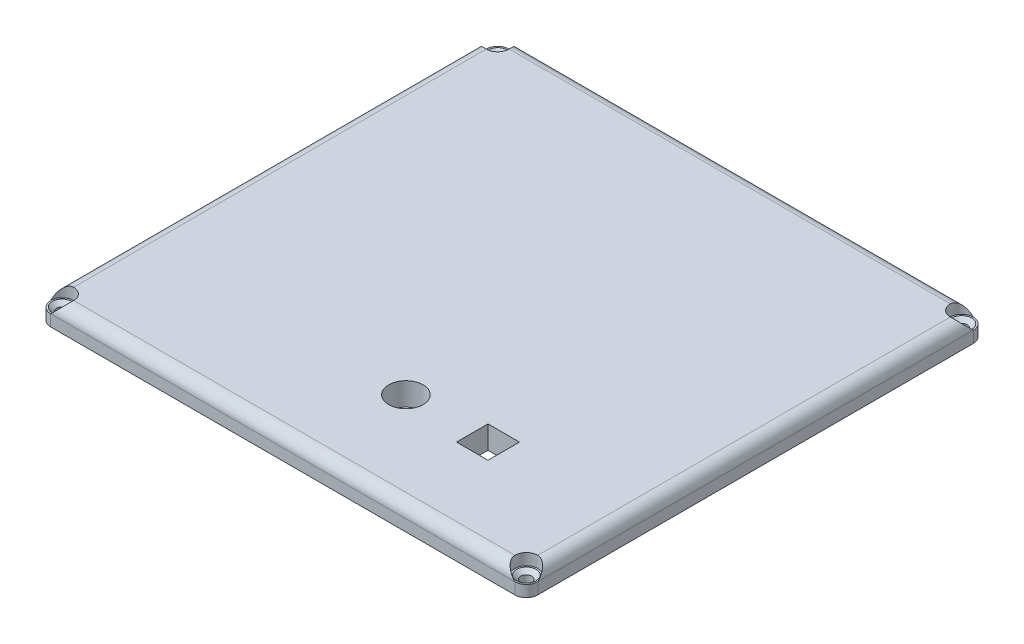
SolidWorks part; units mm, degrees
ref_plane "Front Plane" through (0, 0, 0) normal (0, 0, 1) x (1, 0, 0)
ref_plane "Top Plane" through (0, 0, 0) normal (0, 1, 0) x (1, 0, 0)
ref_plane "Right Plane" through (0, 0, 0) normal (1, 0, 0) x (0, 0, -1)
sketch "Sketch1" plane through (0, 0, 0) normal (0, 1, 0) x (1, 0, 0)
  line L1 (-53.975, -50.8) -> (53.975, -50.8)
  line L2 (-53.975, -50.8) -> (-53.975, 50.8)
  line L3 (-53.975, 50.8) -> (53.975, 50.8)
  line L4 (53.975, -50.8) -> (53.975, 50.8)
  line L5 (-53.975, -50.8) -> (53.975, 50.8) construction
  line L6 (-53.975, 50.8) -> (53.975, -50.8) construction
  point P0 (0, 0)
  dimension "D1" = 107.95
  dimension "D2" = 101.6
extrude "Boss-Extrude1" add sketch "Sketch1" along normal blind 5.08
fillet "Fillet1" radius 2.54 8 edges at (-53.975, 2.54, -50.8) (0, 5.08, -50.8) (-53.975, 5.08, 0) (0, 5.08, 50.8) (53.975, 5.08, 0) (53.975, 2.54, -50.8) (53.975, 2.54, 50.8) (-53.975, 2.54, 50.8)
sketch "Sketch2" plane through (0, 0, 0) normal (0, -1, 0) x (1, 0, 0)
  line L1 (-49.2125, -46.0375) -> (49.2125, -46.0375)
  line L2 (-49.2125, -46.0375) -> (-49.2125, 46.0375)
  line L3 (-49.2125, 46.0375) -> (49.2125, 46.0375)
  line L4 (49.2125, -46.0375) -> (49.2125, 46.0375)
  line L5 (-49.2125, -46.0375) -> (49.2125, 46.0375) construction
  line L6 (-49.2125, 46.0375) -> (49.2125, -46.0375) construction
  line L7 (-46.4973, -43.4975) -> (46.4973, -43.4975)
  line L8 (-46.4973, -43.4975) -> (-46.4973, 43.4975)
  line L9 (-46.4973, 43.4975) -> (46.4973, 43.4975)
  line L10 (46.4973, -43.4975) -> (46.4973, 43.4975)
  line L11 (-46.4973, -43.4975) -> (46.4973, 43.4975) construction
  line L12 (-46.4973, 43.4975) -> (46.4973, -43.4975) construction
  point P0 (0, 0)
  point P6 (0, 0)
  point P11 (49.2125, 46.0375)
  dimension "D3" = 2.54
extrude "Boss-Extrude2" add sketch "Sketch2" along normal blind 2.54
sketch "Sketch3" plane through (0, 0, 0) normal (0, -1, 0) x (1, 0, 0)
  circle A0 centre (6.0087, 29.5186) radius 3.81
  dimension "D1" = 7.62
extrude "Cut-Extrude1" cut sketch "Sketch3" against normal up to surface (5.08 mm away) up to face at (0, 5.08, 0)
sketch "Sketch4" plane through (0, 0, 0) normal (0, -1, 0) x (1, 0, 0)
  line L0 (20.7008, 33.0108) -> (27.6858, 26.0258) construction
  line L1 (20.7008, 33.0108) -> (27.6858, 33.0108)
  line L2 (20.7008, 33.0108) -> (20.7008, 26.0258)
  line L3 (20.7008, 26.0258) -> (27.6858, 26.0258)
  line L4 (27.6858, 33.0108) -> (27.6858, 26.0258)
  point P6 (24.1933, 29.5183)
  point P7 (24.1933, 29.5183)
  dimension "D1" = 6.985
extrude "Cut-Extrude2" cut sketch "Sketch4" against normal up to surface (5.08 mm away) up to face at (6.0087, 5.08, 25.7086)
sketch "Sketch5" plane through (0, 5.08, 0) normal (0, 1, 0) x (1, 0, 0)
  circle A0 centre (-51.435, -48.26) radius 2.54
extrude "Cut-Extrude3" cut sketch "Sketch5" against normal blind 2.54
pattern_linear "LPattern1" count 2 spacing 96.52 along (0, 0, -1) count 2 spacing 102.87 along (1, 0, 0) of "Cut-Extrude3"
hole_wizard "CSK for #2 Flat Head Machine Screw (100)1" positions "Sketch6" profile "Sketch7" countersink size "#2" standard "ANSI Inch" end condition through all
sketch "Sketch6" plane through (0, 2.54, 0) normal (0, 1, 0) x (1, 0, 0)
  point P0 (51.435, -48.26)
  point P3 (-51.435, -48.26)
  point P6 (-51.435, 48.26)
  point P9 (51.435, 48.26)
sketch "Sketch7" plane through (51.435, 2.54, 48.26) normal (1, 0, 0) x (0, 0, 1)
  line L0 (0, 0) -> (0, 5.08)
  line L1 (0, 5.08) -> (1.2192, 5.08)
  line L2 (1.2192, 5.08) -> (1.2192, 0.8099)
  line L3 (1.2192, 0.8099) -> (2.1844, 0)
  line L5 (2.1844, 0) -> (0, 0)
  line L6 (-1.2192, 0.8099) -> (-2.1844, 0) construction
  line L11 (0, -6.35) -> (0, 107.95) construction
  dimension "Thru Hole Dia." = 2.4384
  dimension "Thru Hole Depth" = 5.08
  dimension "Near C'Sink Dia." = 4.3688
  dimension "Near C'Sink Angle" = 100
